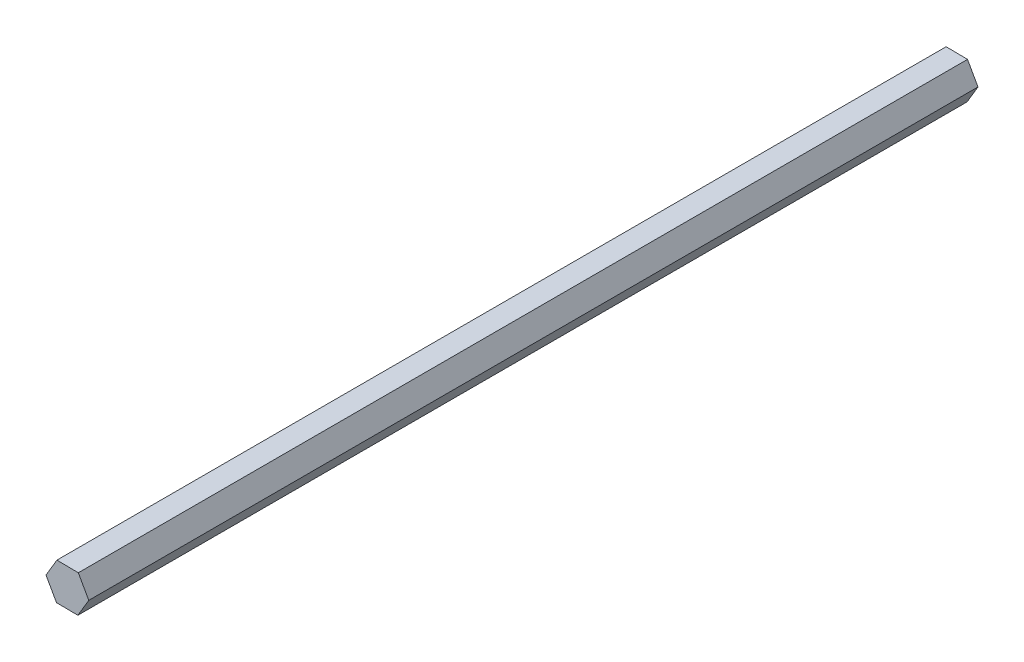
SolidWorks part; units mm, degrees
ref_plane "Front Plane" through (0, 0, 0) normal (0, 0, 1) x (1, 0, 0)
ref_plane "Top Plane" through (0, 0, 0) normal (0, 1, 0) x (1, 0, 0)
ref_plane "Right Plane" through (0, 0, 0) normal (1, 0, 0) x (0, 0, -1)
sketch "Sketch1" plane through (0, 0, 0) normal (0, 0, 1) x (1, 0, 0)
  line L1 (2.8069, 4.729) -> (-2.692, 4.7953)
  line L2 (-2.692, 4.7953) -> (-5.4989, 0.0663)
  line L3 (-5.4989, 0.0663) -> (-2.8069, -4.729)
  line L4 (-2.8069, -4.729) -> (2.692, -4.7953)
  line L5 (2.692, -4.7953) -> (5.4989, -0.0663)
  line L6 (5.4989, -0.0663) -> (2.8069, 4.729)
  circle A0 centre (0, 0) radius 4.7625 construction
  dimension "D1" = 9.525
extrude "Boss-Extrude1" add sketch "Sketch1" along normal blind 228.6
